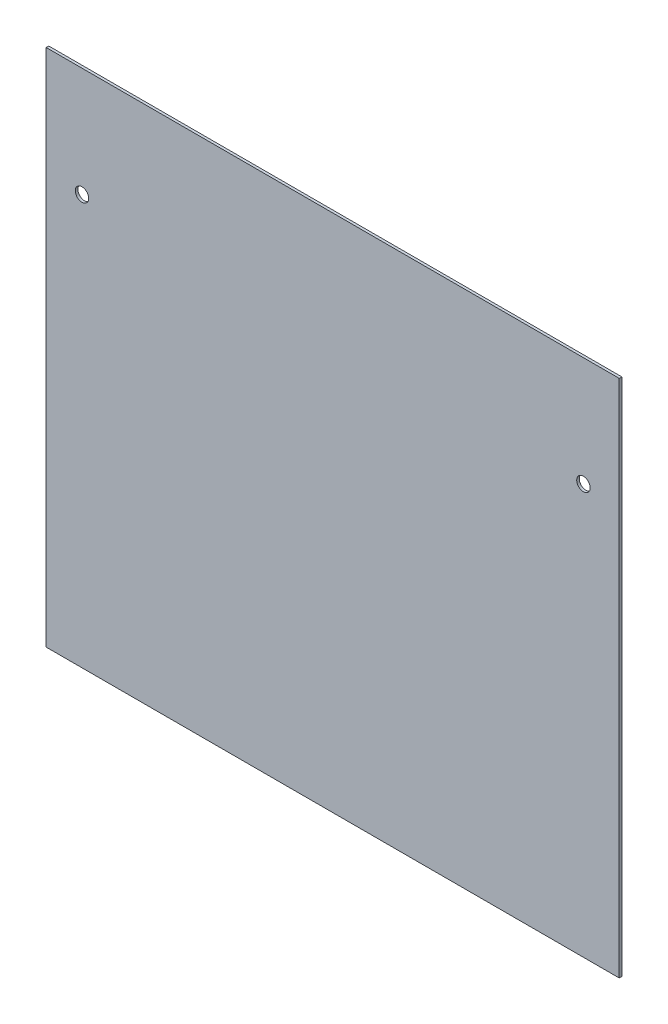
SolidWorks part; units mm, degrees
material "Alumina"
ref_plane "Front Plane" through (0, 0, 0) normal (0, 0, 1) x (1, 0, 0)
ref_plane "Top Plane" through (0, 0, 0) normal (0, 1, 0) x (1, 0, 0)
ref_plane "Right Plane" through (0, 0, 0) normal (1, 0, 0) x (0, 0, -1)
sketch "Sketch2" plane through (0, 0, 0) normal (0, 0, 1) x (1, 0, 0)
  line L1 (-144, 130.5) -> (144, 130.5)
  line L2 (-144, 130.5) -> (-144, -130.5)
  line L3 (-144, -130.5) -> (144, -130.5)
  line L4 (144, 130.5) -> (144, -130.5)
  line L5 (-144, 130.5) -> (144, -130.5) construction
  line L6 (-144, -130.5) -> (144, 130.5) construction
  point P0 (0, 0)
  dimension "D1" = 288
  dimension "D2" = 261
extrude "Boss-Extrude1" add sketch "Sketch2" along normal blind 1.2954
hole_wizard "1/4 Clearance Hole1" positions "Sketch3" profile "Sketch4" hole size "1/4" standard "ANSI Inch" end condition through all
sketch "Sketch3" plane through (0, 0, 1.2954) normal (0, 0, 1) x (1, 0, 0)
  line L0 (-144, 130.5) -> (-144, -130.5) construction
  line L1 (144, -130.5) -> (144, 130.5) construction
  line L3 (144, 130.5) -> (-144, 130.5) construction
  point P0 (-126, 75.5)
  point P2 (126, 75.5)
  point P11 (0, 0)
  point P12 (0, 0)
  point P18 (0, 0)
  dimension "D1" = 18
  dimension "D2" = 18
  dimension "D3" = 55
sketch "Sketch4" plane through (-126, 75.5, 1.2954) normal (1, 0, 0) x (0, -1, 0)
  line L0 (0, 0) -> (0, 1.2954)
  line L1 (0, 1.2954) -> (3.3782, 1.2954)
  line L2 (3.3782, 1.2954) -> (3.3782, 0)
  line L5 (3.3782, 0) -> (0, 0)
  line L11 (0, -6.35) -> (0, 107.95) construction
  dimension "Thru Hole Dia." = 6.7564
  dimension "Thru Hole Depth" = 1.2954
